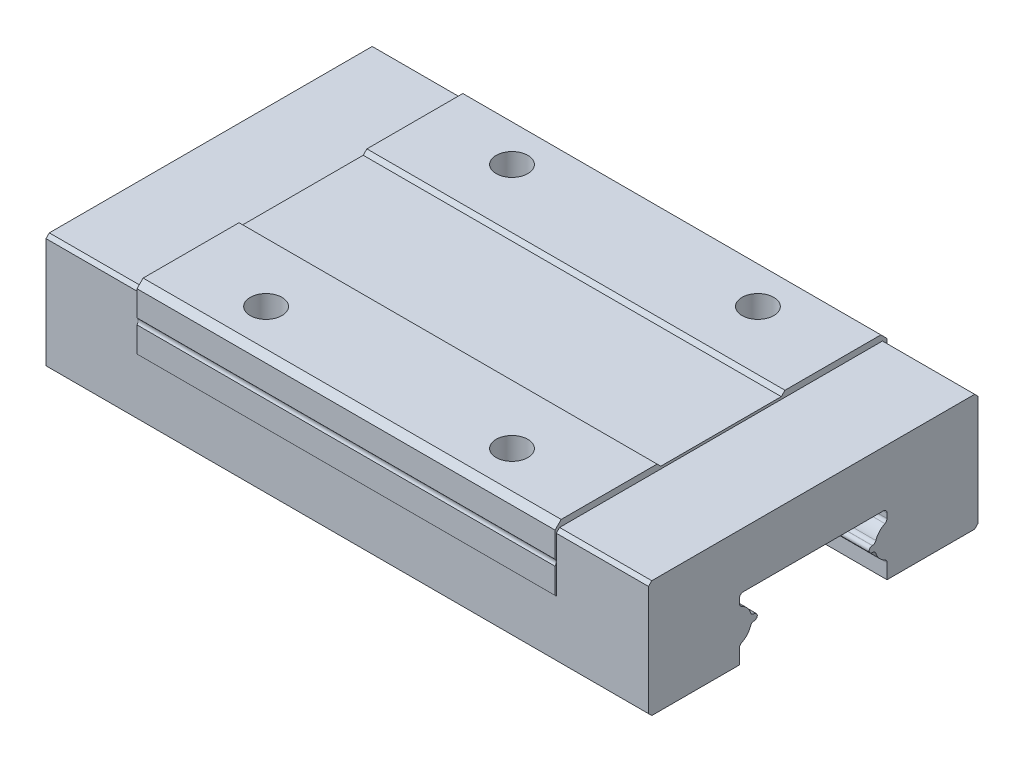
SolidWorks part; units mm, degrees
ref_plane "前视基准面" through (0, 0, 0) normal (0, 0, 1) x (1, 0, 0)
ref_plane "上视基准面" through (0, 0, 0) normal (0, 1, 0) x (1, 0, 0)
ref_plane "右视基准面" through (0, 0, 0) normal (1, 0, 0) x (0, 0, -1)
other "Configuration Table"
ref_plane "基准面1" through (-24.5, 0, 0) normal (-1, 0, 0) x (0, -1, 0)
sketch "草图1" plane through (-24.5, 0, 0) normal (-1, 0, 0) x (0, -1, 0)
  line L0 (1, 13.4) -> (-8.5, 13.4)
  line L1 (-8.5, 13.4) -> (-8.5, -13.4)
  line L2 (-8.5, -13.4) -> (1, -13.4)
  line L3 (1, -13.4) -> (1, -6)
  line L4 (1, -6) -> (-0.4089, -6)
  line L5 (-1.51, -5.04) -> (-1.51, -4.8)
  line L6 (-2.01, -4.8) -> (-2.01, -5.04)
  line L7 (-3.1111, -6) -> (-4, -6)
  line L8 (-4, -6) -> (-4, 6)
  line L9 (-4, 6) -> (-3.1111, 6)
  line L10 (-2.01, 5.04) -> (-2.01, 4.8)
  line L11 (-1.51, 4.8) -> (-1.51, 5.04)
  line L12 (-0.4089, 6) -> (1, 6)
  line L13 (1, 6) -> (1, 13.4)
  arc A0 (-0.4089, -6) -> (-1.51, -5.04) centre (-1.76, -6.4382) ccw
  arc A1 (-1.51, -4.8) -> (-2.01, -4.8) centre (-1.76, -4.8) ccw
  arc A2 (-2.01, -5.04) -> (-3.1111, -6) centre (-1.76, -6.4382) ccw
  arc A3 (-3.1111, 6) -> (-2.01, 5.04) centre (-1.76, 6.4382) ccw
  arc A4 (-2.01, 4.8) -> (-1.51, 4.8) centre (-1.76, 4.8) ccw
  arc A5 (-1.51, 5.04) -> (-0.4089, 6) centre (-1.76, 6.4382) ccw
extrude "凸台-拉伸1" add sketch "草图1" against normal blind 49
sketch "草图2" plane through (0, 0, -13.4) normal (0, 0, -1) x (-1, 0, 0)
  line L0 (17, 8.5) -> (17, 3.8)
  line L1 (17, 3.8) -> (-17, 3.8)
  line L2 (-17, 3.8) -> (-17, 8.5)
  line L3 (-17, 8.5) -> (17, 8.5)
extrude "凸台-拉伸2" add sketch "草图2" along normal blind 0.1
sketch "草图3" plane through (0, 0, 13.4) normal (0, 0, 1) x (1, 0, 0)
  line L0 (17, 8.5) -> (17, 3.9)
  line L1 (17, 3.9) -> (-17, 3.9)
  line L2 (-17, 3.9) -> (-17, 8.5)
  line L3 (-17, 8.5) -> (17, 8.5)
extrude "凸台-拉伸3" add sketch "草图3" along normal blind 0.1
sketch "草图4" plane through (0, 8.5, 0) normal (0, 1, 0) x (-1, 0, 0)
  line L0 (17, 13.5) -> (17, -13.5)
  line L1 (17, -13.5) -> (-17, -13.5)
  line L2 (-17, -13.5) -> (-17, 13.5)
  line L3 (-17, 13.5) -> (17, 13.5)
extrude "凸台-拉伸4" add sketch "草图4" along normal blind 0.5
sketch "草图5" plane through (17, 0, 0) normal (1, 0, 0) x (0, 0, -1)
  line L0 (-13.5, 6.4449) -> (-13.5, 5.9551)
  arc A0 (-13.5, 5.9551) -> (-13.5, 6.4449) centre (-13.75, 6.2) ccw
extrude "切除-拉伸1" cut sketch "草图5" against normal blind 34
sketch "草图6" plane through (17, 0, 0) normal (1, 0, 0) x (0, 0, -1)
  line L0 (4.9, 9) -> (-4.9, 9)
  line L1 (-4.9, 9) -> (-4.9, 8.7)
  line L2 (-4.9, 8.7) -> (4.9, 8.7)
  line L3 (4.9, 8.7) -> (4.9, 9)
extrude "切除-拉伸2" cut sketch "草图6" against normal through all
draft "拔模1" type of draft neutral plane draft angle 45 faces to draft 1 face at (0, 3.9, 13.45) neutral plane through (0, 0, 13.5) neutral plane normal (0, 0, 1) parameters "D1"=45
draft "拔模2" type of draft neutral plane draft angle 45 faces to draft 1 face at (0, 3.8, -13.45) neutral plane through (24.5, 8.5, -13.4) neutral plane normal (0, 0, -1) parameters "D1"=45
draft "拔模3" type of draft neutral plane draft angle 45 faces to draft 2 face at (0, 8.85, 4.9) face at (0, 8.85, -4.9) neutral plane through (-24.5, 8.7, 4.9) neutral plane normal (0, 1, 0) parameters "D1"=45
hole_wizard "M2 间隙孔1" positions "草图8" profile "草图7" hole size "M2" standard "ANSI Metric"
sketch "草图8" plane through (0, 9, 0) normal (0, 1, 0) x (1, 0, 0)
  point P0 (10, -10)
  point P1 (-10, -10)
  point P2 (-10, 10)
  point P3 (10, 10)
sketch "草图7" plane through (10, 9, 10) normal (1, 0, 0) x (0, 0, 1)
  line L0 (0, 0) -> (0, 4.2751)
  line L1 (0, 4.2751) -> (1.29, 3.5)
  line L2 (1.29, 3.5) -> (1.29, 0)
  line L5 (1.29, 0) -> (0, 0)
  line L10 (0, 4.2751) -> (-1.29, 3.5) construction
  line L11 (0, -6.35) -> (0, 107.95) construction
  dimension "孔直径" = 2.58
  dimension "孔深度" = 3.5
  dimension "导头角度" = 118
chamfer "倒角1" distance 0.27 angle 45 6 edges at (0, -1, -13.4) (-20.75, 8.5, -13.4) (0, -1, 13.4) (-20.75, 8.5, 13.4) (20.75, 8.5, -13.4) (20.75, 8.5, 13.4)
chamfer "倒角2" distance 0.5 angle 45 2 edges at (0, 9, 13.5) (0, 9, -13.5)
fillet "圆角1" radius 0.3 10 edges at (0, 0.4089, -6) (0, 0.4089, 6) (0, 2.01, -5.04) (0, 4, 6) (0, 3.1111, -6) (0, 3.1111, 6) (0, 1.51, -5.04) (0, 2.01, 5.04) (0, 1.51, 5.04) (0, 4, -6)
